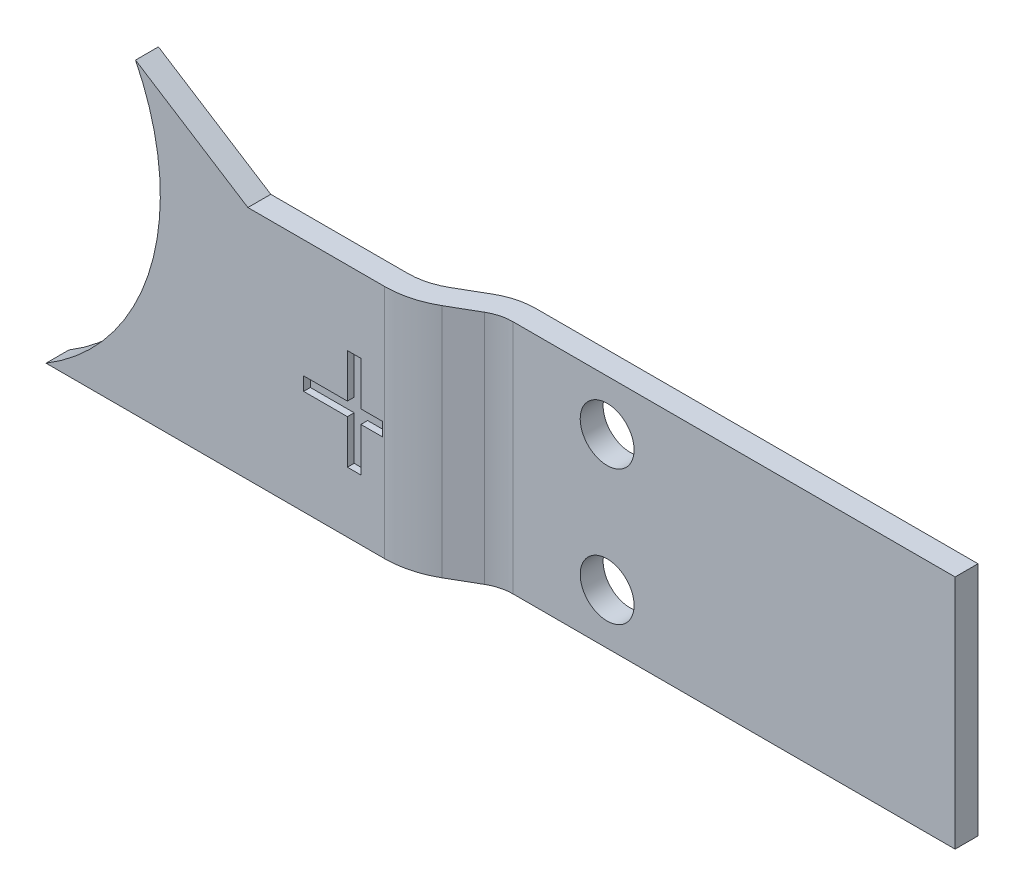
SolidWorks part; units mm, degrees
ref_plane "前视基准面" through (0, 0, 0) normal (0, 0, 1) x (1, 0, 0)
ref_plane "上视基准面" through (0, 0, 0) normal (0, 1, 0) x (1, 0, 0)
ref_plane "右视基准面" through (0, 0, 0) normal (1, 0, 0) x (0, 0, -1)
sketch "Sketch1" plane through (0, 0, 0) normal (0, 0, 1) x (1, 0, 0)
  line L0 (0, -30) -> (80, -30)
  line L1 (80, -30) -> (80, 5)
  line L2 (80, 5) -> (48, 5)
  line L4 (48, 5) -> (16.1141, 25.3049)
  arc A0 (16.1141, 25.3049) -> (0, -30) centre (0, 0) ccw
  dimension "D1" = 80
  dimension "D2" = 60
  dimension "D3" = 35
  dimension "D4" = 32
extrude "Boss-Extrude1" add sketch "Sketch1" along normal blind 3.4
sketch "Sketch2" plane through (0, 0, 3.4) normal (0, 0, 1) x (1, 0, 0)
  circle A0 centre (48, -12.5) radius 2.75
  circle A3 centre (48, -12.5) radius 2
  dimension "D2" = 5.5
sketch "Sketch3" plane through (0, 0, 3.4) normal (0, 0, 1) x (1, 0, 0)
  circle A0 centre (0, 0) radius 5
  dimension "D1" = 10
extrude "Cut-Extrude1" cut sketch "Sketch3" against normal blind 6
sketch "Sketch5" plane through (0, 0, 3.4) normal (0, 0, 1) x (1, 0, 0)
  line L0 (0, 20) -> (0, 0) construction
  line L1 (0, 0) -> (-18.1865, -10.5) construction
  arc A0 (0, 10) -> (-8.6603, -5) centre (0, 0) ccw
  arc A2 (0, 18) -> (-15.5885, -9) centre (0, 0) ccw
  arc A3 (-8.6603, -5) -> (-15.5885, -9) centre (-12.1244, -7) cw
  arc A4 (0, 18) -> (0, 10) centre (0, 14) cw
  point P4 (0, 18)
  point P6 (0, 10)
  point P8 (-8.6603, -5)
  point P9 (-15.5885, -9)
  dimension "D1" = 120
  dimension "D2" = 21
extrude "Cut-Extrude2" cut sketch "Sketch5" against normal blind 10
sketch "Sketch6" plane through (0, 0, 0) normal (0, 0, -1) x (-1, 0, 0)
  circle A0 centre (0, 0) radius 35
extrude "Cut-Extrude3" cut sketch "Sketch6" against normal blind 10
sketch "Sketch7" plane through (0, 0, 3.4) normal (0, 0, 1) x (1, 0, 0)
  line L0 (62.7754, -14.5) -> (62.7754, -21)
  line L1 (64.7754, -6) -> (62.7754, -6)
  line L2 (64.7754, -6) -> (64.7754, -12.5)
  line L3 (64.7754, -21) -> (62.7754, -21)
  line L4 (62.7754, -6) -> (62.7754, -12.5)
  line L7 (80, -30) -> (80, 5) construction
  line L8 (62.7754, -12.5) -> (56.2754, -12.5)
  line L9 (71.2754, -12.5) -> (64.7754, -12.5)
  line L10 (71.2754, -12.5) -> (71.2754, -14.5)
  line L11 (71.2754, -14.5) -> (64.7754, -14.5)
  line L12 (56.2754, -12.5) -> (56.2754, -14.5)
  line L17 (62.7754, -14.5) -> (56.2754, -14.5)
  line L18 (63.9087, -14.5) -> (63.642, -14.5)
  line L19 (64.7754, -14.5) -> (64.7754, -21)
  point P0 (63.9087, -12.5)
  point P9 (80, -12.5)
  point P10 (63.7754, -13.5)
  dimension "D1" = 15
  dimension "D2" = 2
  dimension "D3" = 0
  dimension "D4" = 2
  dimension "D5" = 15
extrude "Cut-Extrude4" cut sketch "Sketch7" against normal blind 1
sketch "Sketch8" plane through (0, 0, 0) normal (0, 0, -1) x (-1, 0, 0)
  line L0 (-80, 5) -> (-48, 5) construction
  line L1 (-80, -30) -> (-68, -30)
  line L2 (-80, -30) -> (-80, 5)
  line L3 (-80, 5) -> (-68, 5)
  line L4 (-68, -30) -> (-68, 5)
  dimension "D1" = 20
extrude "Cut-Extrude5" cut sketch "Sketch8" against normal up to next
sketch "Sketch9" plane through (0, 5, 0) normal (0, 1, 0) x (1, 0, 0)
  line L0 (68, 0) -> (68.3205, 0)
  line L1 (83, 5) -> (148, 5)
  line L2 (73.3205, 1.3397) -> (77.3397, 3.6603)
  line L3 (68, -3.4) -> (68.3205, -3.4)
  line L4 (75.0205, -1.6047) -> (79.0397, 0.7158)
  line L5 (82.3397, 5) -> (83, 5)
  line L6 (68, 0) -> (48, 0) construction
  line L7 (82.3397, 1.6) -> (83, 1.6)
  line L8 (83, 1.6) -> (148, 1.6)
  line L9 (68, 0) -> (68, -3.4)
  line L10 (148, 1.6) -> (148, 5)
  arc A0 (77.3397, 3.6603) -> (82.3397, 5) centre (82.3397, -5) cw
  arc A1 (68.3205, 0) -> (73.3205, 1.3397) centre (68.3205, 10) ccw
  arc A2 (68.3205, -3.4) -> (75.0205, -1.6047) centre (68.3205, 10) ccw
  arc A3 (79.0397, 0.7158) -> (82.3397, 1.6) centre (82.3397, -5) cw
  point P11 (68, 0)
  dimension "D1" = 15
  dimension "D4" = 10
  dimension "D2" = 5
  dimension "D3" = 150
  dimension "D6" = 65
  dimension "D5" = 3.4
extrude "Boss-Extrude2" add sketch "Sketch9" against normal up to surface (35 mm away) up to face at (43.0139, -30, 1.7)
sketch "Sketch10" plane through (0, 0, -5) normal (0, 0, -1) x (-1, 0, 0)
  line L0 (-96.3397, 5) -> (-96.3397, -30) construction
  line L1 (-148, 5) -> (-82.3397, 5) construction
  line L2 (-82.3397, -30) -> (-148, -30) construction
  line L3 (-82.3397, -30) -> (-82.3397, 5) construction
  line L4 (-82.3397, -12.5) -> (-106.6658, -12.5) construction
  circle A0 centre (-96.3397, -2.5) radius 4
  circle A1 centre (-96.3397, -22.5) radius 4
  dimension "D2" = 10
  dimension "D1" = 14
extrude "Cut-Extrude6" cut sketch "Sketch10" against normal blind 10
